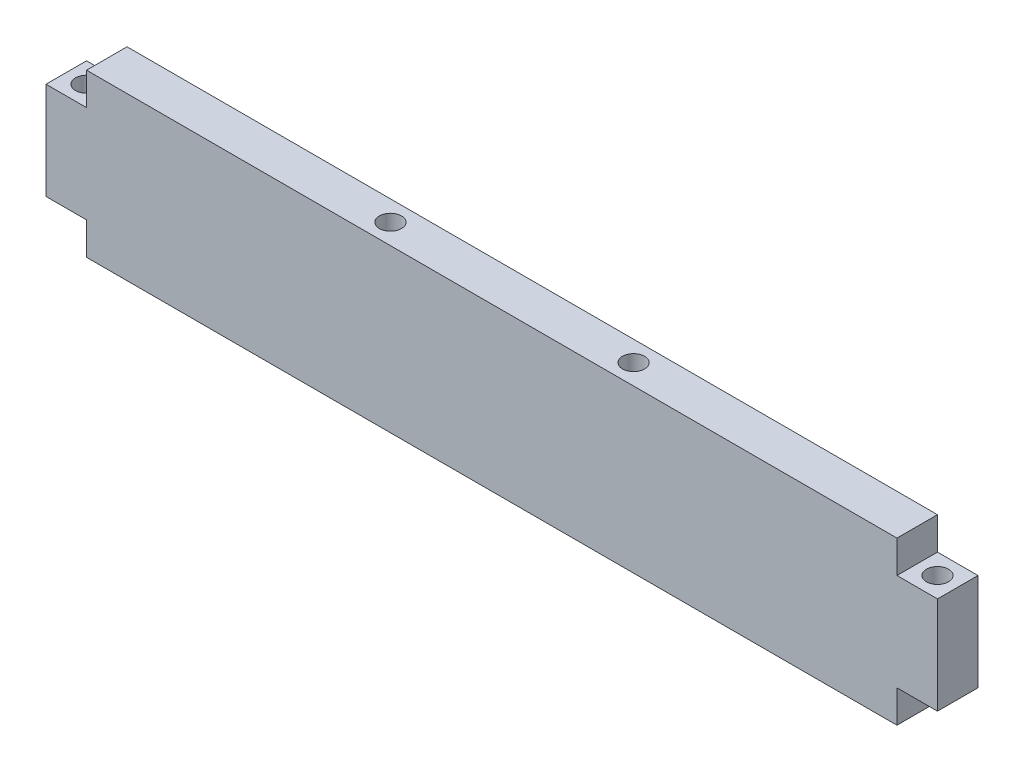
SolidWorks part; units mm, degrees
material "6061 Alloy"
ref_plane "Front Plane" through (0, 0, 0) normal (0, 0, 1) x (1, 0, 0)
ref_plane "Top Plane" through (0, 0, 0) normal (0, 1, 0) x (1, 0, 0)
ref_plane "Right Plane" through (0, 0, 0) normal (1, 0, 0) x (0, 0, -1)
sketch "Sketch1" plane through (0, 0, 0) normal (0, 0, 1) x (1, 0, 0)
  line L1 (-69.85, -12.7) -> (69.85, -12.7)
  line L2 (-69.85, -12.7) -> (-69.85, 12.7)
  line L3 (-69.85, 12.7) -> (69.85, 12.7)
  line L4 (69.85, -12.7) -> (69.85, 12.7)
  line L5 (-69.85, -12.7) -> (69.85, 12.7) construction
  line L6 (-69.85, 12.7) -> (69.85, -12.7) construction
  point P0 (0, 0)
  dimension "D1" = 25.4
  dimension "D2" = 139.7
extrude "Boss-Extrude1" add sketch "Sketch1" along normal mid plane 6.35
sketch "Sketch2" plane through (0, 0, 3.175) normal (0, 0, 1) x (1, 0, 0)
  line L0 (-69.85, 12.7) -> (-69.85, -12.7) construction
  line L1 (-69.85, 7.62) -> (-63.5, 7.62)
  line L3 (-69.85, -7.62) -> (-63.5, -7.62)
  line L5 (69.85, -12.7) -> (69.85, 12.7) construction
  line L6 (69.85, 7.62) -> (63.5, 7.62)
  line L8 (69.85, -7.62) -> (63.5, -7.62)
  line L10 (69.85, 12.7) -> (-69.85, 12.7) construction
  line L11 (-69.85, -12.7) -> (69.85, -12.7) construction
  line L12 (-69.85, 7.62) -> (-69.85, 12.7)
  line L13 (-69.85, 12.7) -> (-63.5, 12.7)
  line L14 (-63.5, 12.7) -> (-63.5, 7.62)
  line L15 (-63.5, -7.62) -> (-63.5, -12.7)
  line L16 (-63.5, -12.7) -> (-69.85, -12.7)
  line L17 (-69.85, -12.7) -> (-69.85, -7.62)
  line L18 (63.5, 7.62) -> (63.5, 12.7)
  line L19 (63.5, 12.7) -> (69.85, 12.7)
  line L20 (69.85, 12.7) -> (69.85, 7.62)
  line L21 (69.85, -7.62) -> (69.85, -12.7)
  line L22 (69.85, -12.7) -> (63.5, -12.7)
  line L23 (63.5, -12.7) -> (63.5, -7.62)
  dimension "D1" = 6.35
  dimension "D2" = 5.08
  dimension "D3" = 5.08
extrude "Cut-Extrude1" cut sketch "Sketch2" against normal up to next
sketch "Sketch3" plane through (0, 12.7, 0) normal (0, 1, 0) x (1, 0, 0)
  line L0 (-69.85, 0) -> (69.85, 0) construction
  line L1 (-69.85, 3.175) -> (-69.85, -3.175) construction
  line L2 (69.85, 3.175) -> (69.85, -3.175) construction
  point P6 (-66.675, 0)
  point P7 (-19.05, 0)
  point P8 (19.05, 0)
  point P9 (66.675, 0)
  dimension "D1" = 3.175
  dimension "D2" = 50.8
  dimension "D3" = 50.8
  dimension "D4" = 3.175
hole_wizard "Tap Drill for #8-32 Tap1" positions "Sketch4" profile "Sketch5" hole size "#8-32" standard "ANSI Inch"
sketch "Sketch4" plane through (0, 12.7, 0) normal (0, 1, 0) x (1, 0, 0)
  point P0 (-66.675, 0)
  point P3 (-19.05, 0)
  point P6 (19.05, 0)
  point P9 (66.675, 0)
sketch "Sketch5" plane through (-66.675, 12.7, 0) normal (1, 0, 0) x (0, 0, 1)
  line L0 (0, 0) -> (0, 13.7378)
  line L1 (0, 13.7378) -> (1.7272, 12.7)
  line L2 (1.7272, 12.7) -> (1.7272, 0)
  line L5 (1.7272, 0) -> (0, 0)
  line L10 (0, 13.7378) -> (-1.7272, 12.7) construction
  line L11 (0, -6.35) -> (0, 107.95) construction
  dimension "Hole Dia." = 3.4544
  dimension "Hole Depth" = 12.7
  dimension "Drill Angle" = 118
mirror "Mirror1" about plane through (0, 0, 0) normal (0, 1, 0) of "Tap Drill for #8-32 Tap1"
